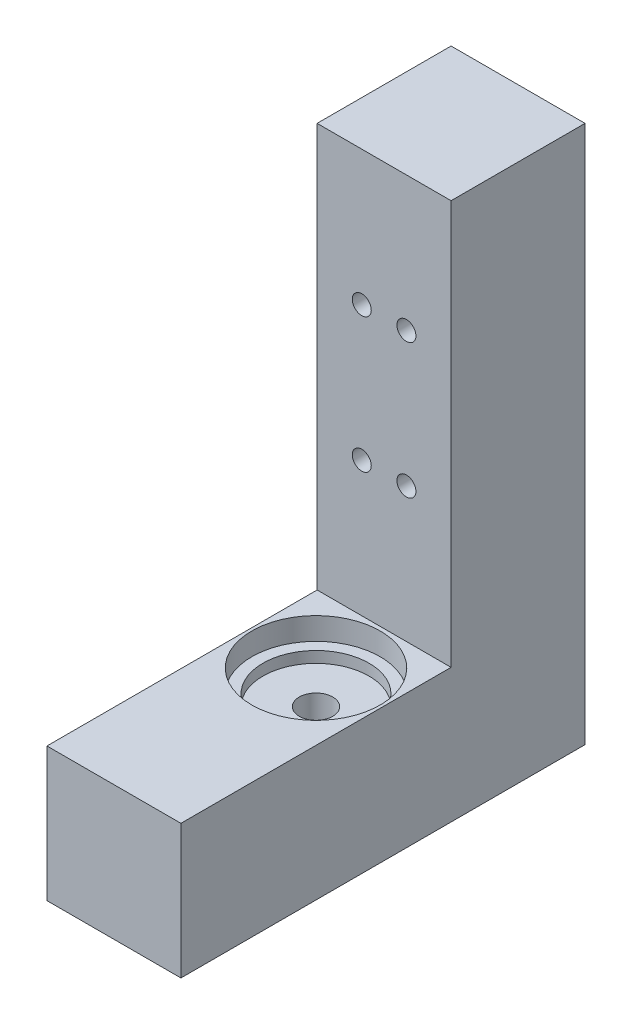
SolidWorks part; units mm, degrees
ref_plane "Front Plane" through (0, 0, 0) normal (0, 0, 1) x (1, 0, 0)
ref_plane "Top Plane" through (0, 0, 0) normal (0, 1, 0) x (1, 0, 0)
ref_plane "Right Plane" through (0, 0, 0) normal (1, 0, 0) x (0, 0, -1)
sketch "Sketch2" plane through (0, 0, 0) normal (1, 0, 0) x (0, 0, -1)
  line L1 (0, 0) -> (-72.4, 0)
  line L2 (0, 0) -> (0, 24)
  line L3 (0, 24) -> (-72.4, 24)
  line L4 (-72.4, 0) -> (-72.4, 24)
  dimension "D1" = 72.4
  dimension "D2" = 24
extrude "Boss-Extrude3" add sketch "Sketch2" along normal blind 24
sketch "Sketch5" plane through (0, 24, 0) normal (0, 1, 0) x (1, 0, 0)
  line L0 (24, 0) -> (24, -72.4) construction
  line L1 (0, 0) -> (24, 0)
  line L2 (0, 0) -> (0, -24)
  line L3 (0, -24) -> (24, -24)
  line L4 (24, 0) -> (24, -24)
  dimension "D1" = 24
extrude "Boss-Extrude4" add sketch "Sketch5" along normal blind 72.4
sketch "Sketch6" plane through (0, 0, 24) normal (0, 0, 1) x (1, 0, 0)
  line L0 (0, 96.4) -> (24, 96.4) construction
  line L1 (0, 96.4) -> (0, 24) construction
  circle A0 centre (8, 72.2667) radius 1.7
  dimension "D1" = 3.4
  dimension "D2" = 24.1333
  dimension "D3" = 8
extrude "Cut-Extrude2" cut sketch "Sketch6" against normal through all both and the other way through all
pattern_linear "LPattern1" count 2 spacing 8 along (1, 0, 0) count 2 spacing 24.13 along (0, -1, 0) of "Cut-Extrude2"
sketch "Sketch7" plane through (0, 24, 0) normal (0, 1, 0) x (1, 0, 0)
  line L0 (24, -24) -> (24, -72.4) construction
  line L1 (24, -72.4) -> (0, -72.4) construction
  circle A0 centre (12, -36.2) radius 11.5
  dimension "D3" = 23
  dimension "D1" = 12
  dimension "D2" = 36.2
extrude "Cut-Extrude3" cut sketch "Sketch7" against normal blind 4
sketch "Sketch8" plane through (0, 20, 0) normal (0, 1, 0) x (1, 0, 0)
  circle A0 centre (12, -36.2) radius 9.5
  circle A1 centre (12, -36.2) radius 11.5 construction
  dimension "D1" = 19
extrude "Cut-Extrude4" cut sketch "Sketch8" against normal blind 2
sketch "Sketch9" plane through (0, 18, 0) normal (0, 1, 0) x (1, 0, 0)
  circle A0 centre (12, -36.2) radius 3
  circle A1 centre (12, -36.2) radius 9.5 construction
  dimension "D1" = 6
extrude "Cut-Extrude5" cut sketch "Sketch9" against normal blind 7
equation "\"h\"= 24'Height of the cross section (mm)"
equation "\"B\" = 24'Base of the cross section (mm)"
equation "\"L\"= 72.4'Length of the feature (mm)"
equation "\"d1\" = 23'Outer Diamater of Base (mm)"
equation "\"d2\" = 19'Second Diameter of Base (mm)"
equation "\"d3\"= 6'Last diameter of base (mm)"
equation "\"S\"= 3.4'Hole for the bolt (mm)"
equation "\"Sb\" = \"B\" / 3'Horizontial location of bolt (mm)"
equation "\"Sl\" = \"L\" / 3'Vertical Location of bolt (mm)"
equation "\"D3@Sketch7\"=\"d1\""
equation "\"D1@Sketch7\"=\"B\"/2"
equation "\"D2@Sketch7\"=\"L\"/2"
equation "\"D1@Sketch8\"=\"d2\""
equation "\"D1@Sketch9\"=\"d3\""
equation "\"D1@Sketch6\"=\"S\""
equation "\"D2@Sketch6\"=\"Sl\""
equation "\"D3@Sketch6\"=\"Sb\""
equation "\"D1@Boss-Extrude4\"=\"L\""
equation "\"D1@Sketch2\"=\"L\""
equation "\"D2@Sketch2\"=\"h\""
